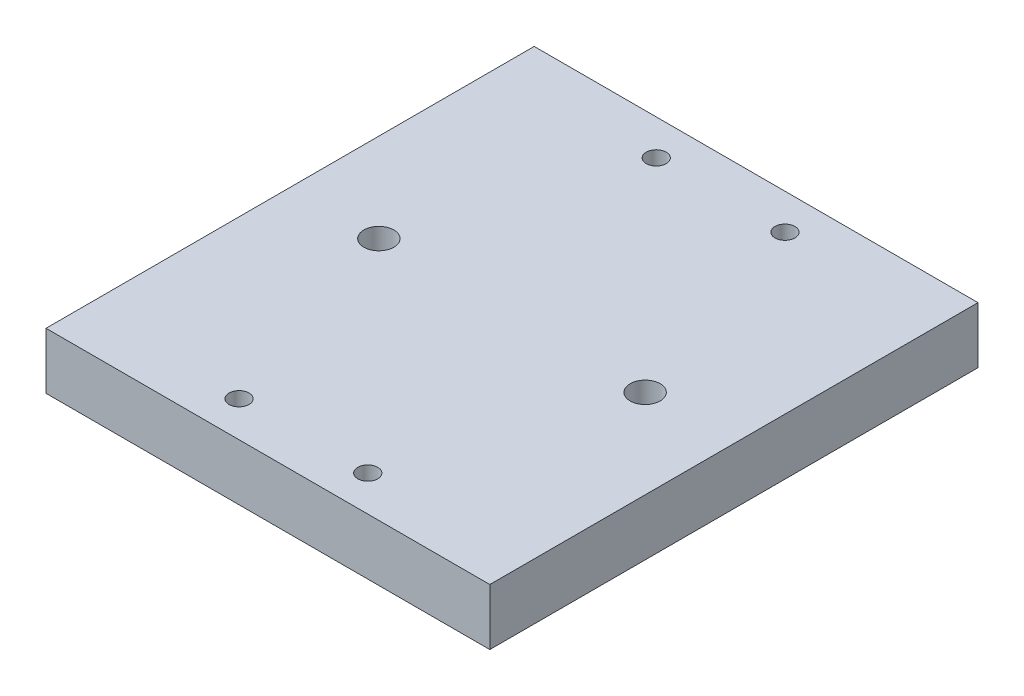
SolidWorks part; units mm, degrees
ref_plane "Alzado" through (0, 0, 0) normal (0, 0, 1) x (1, 0, 0)
ref_plane "Planta" through (0, 0, 0) normal (0, 1, 0) x (1, 0, 0)
ref_plane "Vista lateral" through (0, 0, 0) normal (1, 0, 0) x (0, 0, -1)
sketch "Sketch1" plane through (0, 0, 0) normal (0, 0, 1) x (1, 0, 0)
  line L1 (50, 6.35) -> (-50, 6.35)
  line L2 (50, 6.35) -> (50, -6.35)
  line L3 (50, -6.35) -> (-50, -6.35)
  line L4 (-50, 6.35) -> (-50, -6.35)
  line L5 (50, 6.35) -> (-50, -6.35) construction
  line L6 (50, -6.35) -> (-50, 6.35) construction
  point P0 (0, 0)
  dimension "D1" = 12.7
  dimension "D2" = 100
extrude "Boss-Extrude1" add sketch "Sketch1" along normal mid plane 110
hole_wizard "M4 Tapped Hole1" positions "Sketch2" profile "Sketch3" tap size "M4" standard "DIN"
sketch "Sketch2" plane through (0, 6.35, 0) normal (0, 1, 0) x (1, 0, 0)
  line L0 (-15, 25) -> (15, 25) construction
  line L1 (-15, 25) -> (-15, 0) construction
  point P0 (-15, 25)
  point P7 (15, 25)
  point P8 (15, 0)
  point P9 (15, -25)
  point P10 (-15, 0)
  point P11 (-15, -25)
  dimension "D1" = 25
  dimension "D2" = 15
  dimension "D5" = 30
  dimension "D6" = 25
  dimension "D3" = 2
  dimension "D4" = 3
sketch "Sketch3" plane through (-15, 6.35, -25) normal (1, 0, 0) x (0, 0, 1)
  line L0 (0, 0) -> (0, 9.9914)
  line L1 (0, 9.9914) -> (1.65, 9)
  line L2 (1.65, 9) -> (1.65, 8)
  line L3 (1.65, 8) -> (2, 8)
  line L4 (2, 8) -> (2, 0)
  line L5 (2, 0) -> (0, 0)
  line L10 (0, 9.9914) -> (-1.65, 9) construction
  line L11 (0, -6.35) -> (0, 107.95) construction
  dimension "Tap Drill Dia." = 3.3
  dimension "Tap Drill Depth" = 9
  dimension "Thread Major Dia." = 4
  dimension "Thread Depth" = 8
  dimension "Drill Angle" = 118
hole_wizard "M4 Clearance Hole1" positions "Sketch4" profile "Sketch5" hole size "M4" standard "DIN" end condition through all
sketch "Sketch4" plane through (0, 6.35, 0) normal (0, 1, 0) x (1, 0, 0)
  line L4 (14.5, -47) -> (-14.5, -47) construction
  line L5 (14.5, -47) -> (14.5, 47) construction
  point P29 (14.5, -47)
  point P38 (-14.5, -47)
  point P39 (-14.5, 47)
  point P40 (14.5, 47)
  point P45 (0, -47)
  point P47 (14.5, 0)
  dimension "D1" = 90
  dimension "D2" = 29
  dimension "D5" = 2
  dimension "D3" = 94
  dimension "D4" = 2
sketch "Sketch5" plane through (14.5, 6.35, 47) normal (1, 0, 0) x (0, 0, 1)
  line L0 (0, 0) -> (0, 12.7)
  line L1 (0, 12.7) -> (2.25, 12.7)
  line L2 (2.25, 12.7) -> (2.25, 0)
  line L5 (2.25, 0) -> (0, 0)
  line L11 (0, -6.35) -> (0, 107.95) construction
  dimension "Thru Hole Dia." = 4.5
  dimension "Thru Hole Depth" = 12.7
hole_wizard "CBORE for 1/4 Socket Head Cap Screw1" positions "Sketch6" profile "Sketch7" counterbore size "1/4" standard "ANSI Inch" end condition through all
sketch "Sketch6" plane through (0, -6.35, 0) normal (0, -1, 0) x (-1, 0, 0)
  circle A0 centre (-30, 0) radius 3.3782 construction
  circle A1 centre (30, 0) radius 3.3782 construction
  point P0 (30, 0)
  point P2 (-30, 0)
sketch "Sketch7" plane through (-30, -6.35, 0) normal (1, 0, 0) x (0, 0, -1)
  line L0 (0, 0) -> (0, 12.7)
  line L1 (0, 12.7) -> (3.3782, 12.7)
  line L3 (3.3782, 12.7) -> (3.3782, 6.35)
  line L4 (3.3782, 6.35) -> (5.5562, 6.35)
  line L5 (5.5562, 6.35) -> (5.5562, 0)
  line L7 (5.5562, 0) -> (0, 0)
  line L11 (0, -6.35) -> (0, 107.95) construction
  dimension "Thru Hole Dia." = 6.7564
  dimension "Thru Hole Depth" = 12.7
  dimension "C'Bore Dia." = 11.1125
  dimension "C'Bore Depth" = 6.35
